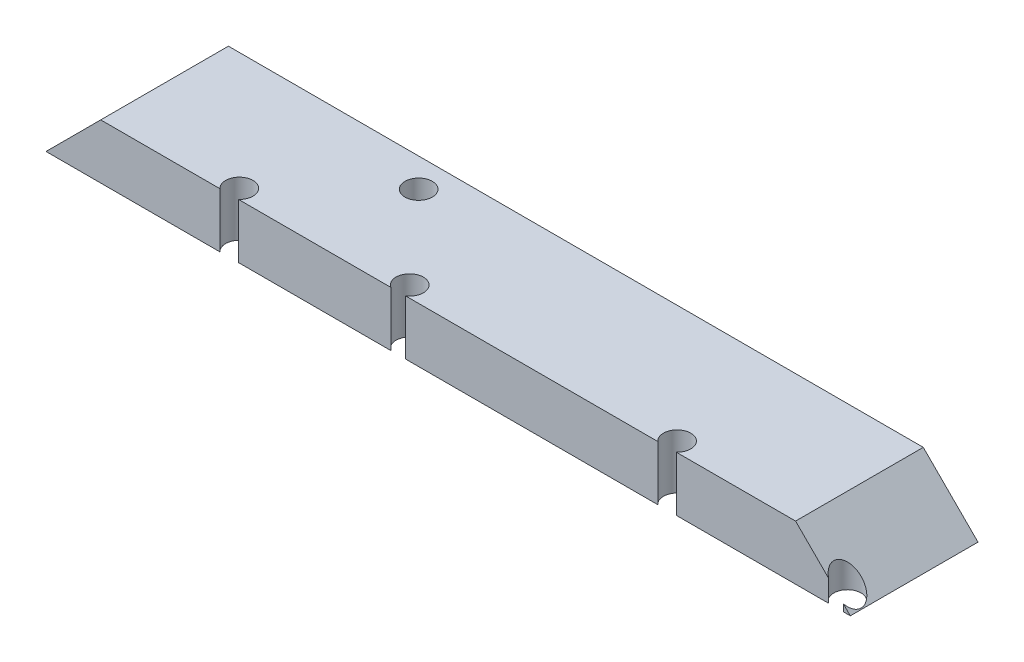
SolidWorks part; units mm, degrees
ref_plane "Front Plane" through (0, 0, 0) normal (0, 0, 1) x (1, 0, 0)
ref_plane "Top Plane" through (0, 0, 0) normal (0, 1, 0) x (1, 0, 0)
ref_plane "Right Plane" through (0, 0, 0) normal (1, 0, 0) x (0, 0, -1)
sketch "Sketch1" plane through (0, 0, 0) normal (0, 1, 0) x (1, 0, 0)
  line L0 (560, 430) -> (560, 10) construction
  line L1 (0, 88.9) -> (560, 88.9)
  line L2 (0, 88.9) -> (0, 0)
  line L3 (0, 0) -> (560, 0)
  line L4 (560, 88.9) -> (560, 0)
  dimension "D1" = 88.9
extrude "Body" add sketch "Sketch1" along normal blind 38.1
sketch "Sketch2" plane through (0, 38.1, 0) normal (0, 1, 0) x (1, 0, 0)
  circle A0 centre (127.6, 7) radius 9.525
  circle A2 centre (190.57, 68.87) radius 9.525
  circle A3 centre (10, 68.87) radius 9.525
  circle A4 centre (245.2, 8.02) radius 9.525
  circle A5 centre (550, 8.02) radius 9.525
  circle A7 centre (432.4, 7) radius 9.525
  dimension "D1" = 19.05
extrude "Mounting hole spacing" cut sketch "Sketch2" against normal up to next
sketch "Sketch3" plane through (0, 0, -88.9) normal (0, 0, -1) x (-1, 0, 0)
  line L0 (-560, 0) -> (-521.9, 38.1)
  line L1 (-560, 38.1) -> (0, 38.1) construction
  line L2 (-521.9, 38.1) -> (-560, 38.1)
  line L3 (-560, 38.1) -> (-560, 0)
  line L4 (-280, 38.1) -> (-280, 0) construction
  line L5 (-560, 0) -> (0, 0) construction
  line L6 (0, 38.1) -> (0, 0)
  line L7 (-38.1, 38.1) -> (0, 38.1)
  line L8 (0, 0) -> (-38.1, 38.1)
extrude "Cut-Extrude1" cut sketch "Sketch3" against normal up to next
